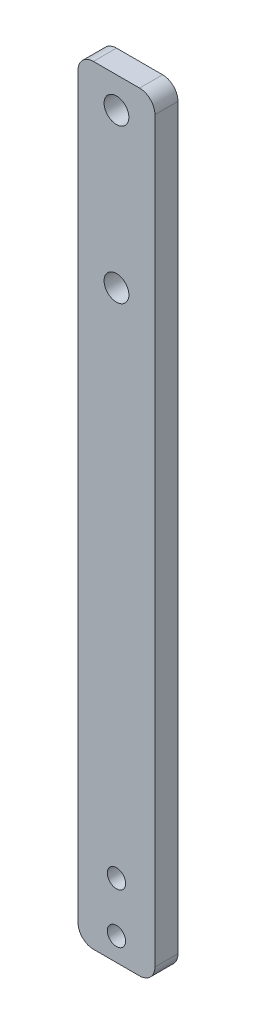
SolidWorks part; units mm, degrees
ref_plane "Front Plane" through (0, 0, 0) normal (0, 0, 1) x (1, 0, 0)
ref_plane "Top Plane" through (0, 0, 0) normal (0, 1, 0) x (1, 0, 0)
ref_plane "Right Plane" through (0, 0, 0) normal (1, 0, 0) x (0, 0, -1)
sketch "Sketch1" plane through (0, 0, 0) normal (0, 0, 1) x (1, 0, 0)
  line L0 (0, 1.625) -> (0, -1.625) construction
  line L2 (2.5, -3.125) -> (-2.5, -3.125)
  line L3 (2.5, -3.125) -> (2.5, 46.875)
  line L4 (2.5, 46.875) -> (-2.5, 46.875)
  line L5 (-2.5, -3.125) -> (-2.5, 46.875)
  circle A0 centre (0, 1.625) radius 0.5956
  circle A1 centre (0, -1.625) radius 0.5956
  circle A2 centre (0, 44.875) radius 0.8064
  circle A3 centre (0, 34.875) radius 0.8064
  point P10 (0, -3.125)
  point P14 (0.0035, 33.9804)
  dimension "D2" = 1.1913
  dimension "D7" = 1.6129
  dimension "D1" = 3.25
  dimension "D3" = 5
  dimension "D4" = 1.5
  dimension "D5" = 50
  dimension "D6" = 10
  dimension "D8" = 2
extrude "Boss-Extrude1" add sketch "Sketch1" along normal blind 1.5
fillet "Fillet1" radius 1 4 edges at (-2.5, 46.875, 0.75) (2.5, 46.875, 0.75) (-2.5, -3.125, 0.75) (2.5, -3.125, 0.75)
